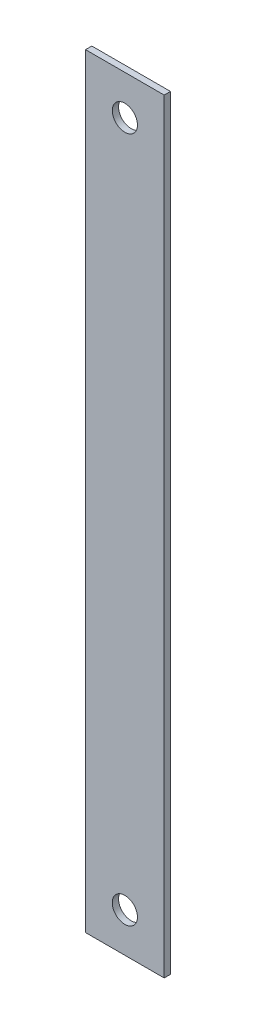
SolidWorks part; units mm, degrees
ref_plane "Front Plane" through (0, 0, 0) normal (0, 0, 1) x (1, 0, 0)
ref_plane "Top Plane" through (0, 0, 0) normal (0, 1, 0) x (1, 0, 0)
ref_plane "Right Plane" through (0, 0, 0) normal (1, 0, 0) x (0, 0, -1)
sketch "Sketch1" plane through (0, 0, 0) normal (0, 0, 1) x (1, 0, 0)
  line L0 (-12.5, 0) -> (12.5, 0) construction
  line L1 (3.5, 121.5) -> (12.5, 121.5)
  line L2 (-12.5, 112.5) -> (-12.5, -105.5)
  line L3 (3.5, -121.5) -> (12.5, -121.5)
  line L4 (12.5, 121.5) -> (12.5, -121.5)
  line L5 (-12.5, 121.5) -> (12.5, -121.5) construction
  line L6 (-12.5, -121.5) -> (12.5, 121.5) construction
  line L7 (-12.5, 112.5) -> (-12.5, 121.5) construction
  line L8 (-12.5, 121.5) -> (3.5, 121.5) construction
  line L9 (-12.5, 112.5) -> (-12.5, 121.5) construction
  line L10 (-12.5, 112.5) -> (-12.5, 121.4821)
  line L11 (3.5, 121.5) -> (0, 121.5)
  line L12 (-12.5, -105.5) -> (-12.5, -115.4875)
  line L13 (3.5, -121.5) -> (0, -121.5)
  line L14 (-12.5, 121.4821) -> (-12.5, 121.5)
  line L15 (-12.5, 121.5) -> (0, 121.5)
  line L16 (-12.5, -115.4875) -> (-12.5, -121.5)
  line L17 (-12.5, -121.5) -> (0, -121.5)
  circle A0 centre (0, 109) radius 4
  circle A1 centre (0, -109) radius 4
  point P0 (0, 0)
  dimension "D4" = 8
  dimension "D1" = 25
  dimension "D3" = 218
  dimension "D6" = 243
extrude "Boss-Extrude1" add sketch "Sketch1" along normal blind 2
